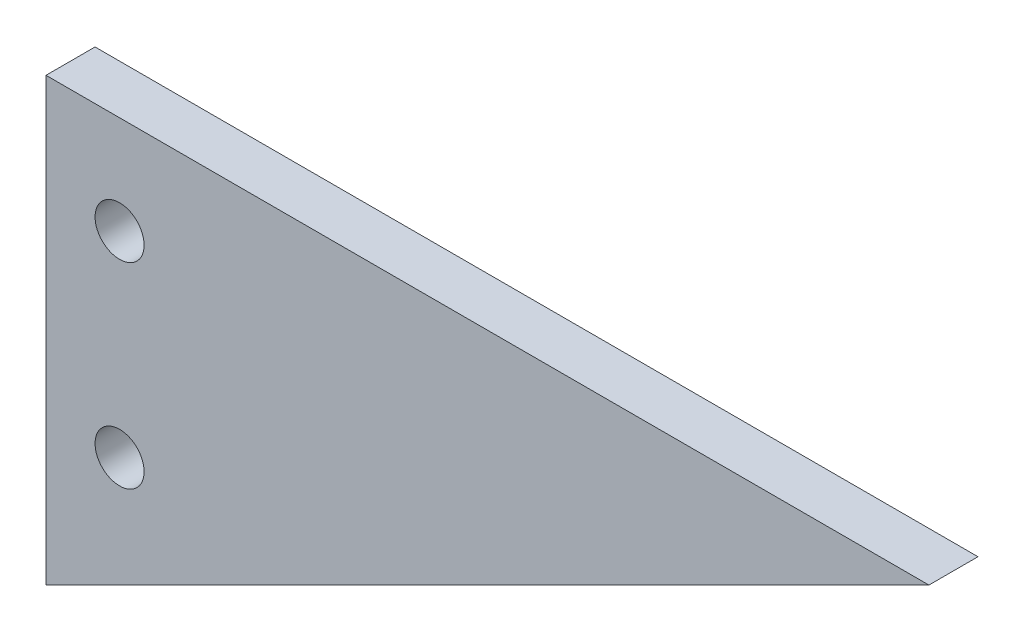
SolidWorks part; units mm, degrees
material "201 Annealed Stainless Steel (SS)"
ref_plane "Front Plane" through (0, 0, 0) normal (0, 0, 1) x (1, 0, 0)
ref_plane "Top Plane" through (0, 0, 0) normal (0, 1, 0) x (1, 0, 0)
ref_plane "Right Plane" through (0, 0, 0) normal (1, 0, 0) x (0, 0, -1)
sketch "Sketch5" plane through (0, 0, 0) normal (0, 0, 1) x (1, 0, 0)
  line L0 (0, 0) -> (180, 0)
  line L1 (180, 0) -> (0, -90)
  line L2 (0, -90) -> (0, 0)
  dimension "D1" = 180
  dimension "D2" = 90
extrude "Boss-Extrude2" add sketch "Sketch5" against normal blind 10
sketch "Sketch6" plane through (0, 0, 0) normal (0, 0, 1) x (1, 0, 0)
  line L0 (0, 0) -> (0, -90) construction
  line L1 (180, 0) -> (0, 0) construction
  circle A0 centre (15, -20) radius 5
  circle A1 centre (15, -60) radius 5
  dimension "D3" = 10
  dimension "D6" = 10
  dimension "D1" = 15
  dimension "D2" = 20
  dimension "D4" = 15
  dimension "D5" = 40
extrude "Cut-Extrude2" cut sketch "Sketch6" against normal through all
ref_plane "Plane1" through (0, 0, -5) normal (0, 0, 1) x (1, 0, 0)
